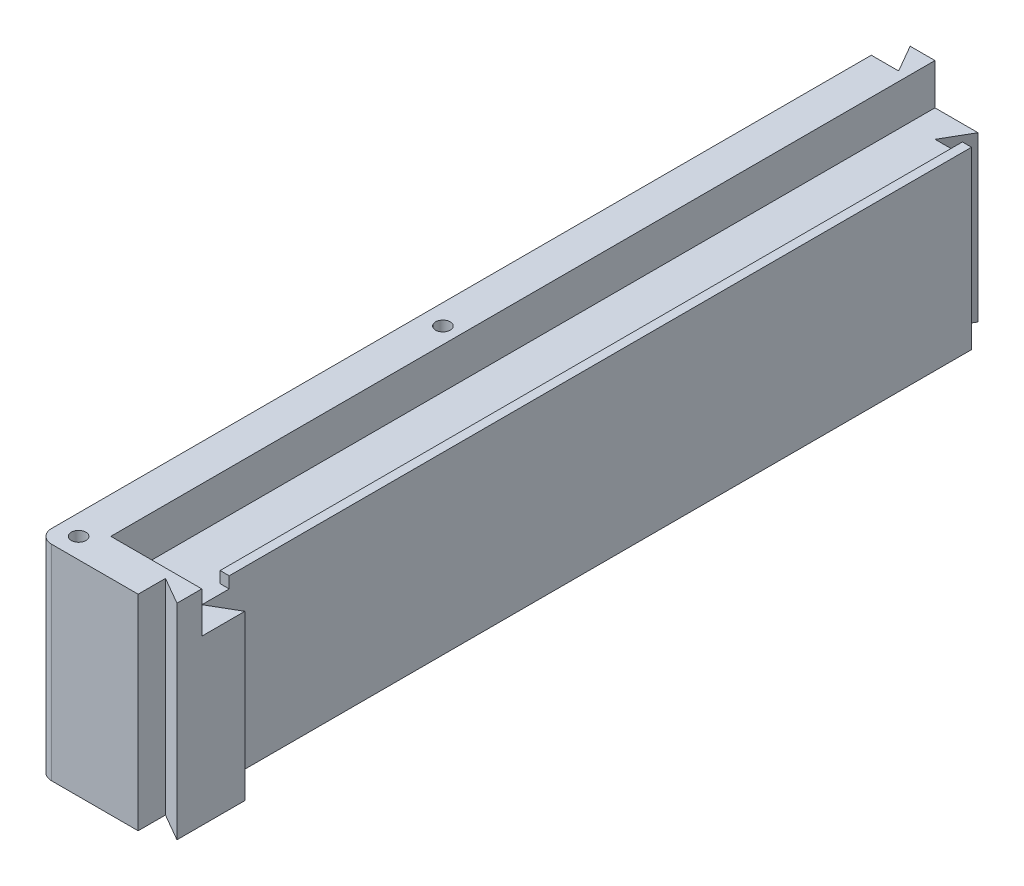
SolidWorks part; units mm, degrees
ref_plane "前视基准面" through (0, 0, 0) normal (0, 0, 1) x (1, 0, 0)
ref_plane "上视基准面" through (0, 0, 0) normal (0, 1, 0) x (1, 0, 0)
ref_plane "右视基准面" through (0, 0, 0) normal (1, 0, 0) x (0, 0, -1)
sketch "草图1" plane through (0, 0, 0) normal (0, 1, 0) x (1, 0, 0)
  line L1 (0, 0) -> (250, 0)
  line L2 (0, 0) -> (0, 350)
  line L3 (0, 350) -> (250, 350)
  line L4 (250, 0) -> (250, 350)
  line L12 (0, 350) -> (-1.1314, 351.1314)
  line L13 (-10, -10) -> (260, -10)
  line L14 (-10, -10) -> (-10, 360)
  line L15 (-10, 360) -> (260, 360)
  line L16 (260, -10) -> (260, 360)
  line L18 (14, 14) -> (236, 14)
  line L19 (14, 14) -> (14, 336)
  line L20 (14, 336) -> (236, 336)
  line L21 (236, 14) -> (236, 336)
  dimension "D7" = 135
  dimension "D1" = 350
  dimension "D2" = 250
  dimension "D3" = 10
  dimension "D4" = 10
  dimension "D5" = 10
  dimension "D6" = 10
  dimension "D8" = 14
  dimension "D9" = 14
  dimension "D10" = 14
  dimension "D11" = 14
extrude "凸台-拉伸2" add sketch "草图1" along normal blind 45
ref_plane "基准面1" through (0, 38.5, 0) normal (0, 1, 0) x (1, 0, 0)
sketch "草图4" plane through (0, 38.5, 0) normal (0, 1, 0) x (1, 0, 0)
  line L0 (0, 0) -> (250, 0) construction
  line L1 (0, 350) -> (250, 350) construction
  line L2 (250, 0) -> (250, 350) construction
  line L3 (0, 0) -> (0, 350) construction
  line L4 (0, 0) -> (250, 0)
  line L5 (0, 350) -> (250, 350)
  line L6 (250, 0) -> (250, 350)
  line L7 (0, 0) -> (0, 350)
  line L9 (14, 14) -> (236, 14)
  line L10 (14, 14) -> (14, 336)
  line L11 (14, 336) -> (236, 336)
  line L12 (236, 14) -> (236, 336)
  dimension "D1" = 14
  dimension "D2" = 14
  dimension "D3" = 14
  dimension "D4" = 14
extrude "凸台-拉伸3" add sketch "草图4" against normal blind 5
sketch "草图9" plane through (0, 38.5, 0) normal (0, 1, 0) x (1, 0, 0)
  line L0 (236, 336) -> (14, 336) construction
  line L1 (236, 14) -> (236, 336) construction
  line L2 (14, 14) -> (236, 14) construction
  line L3 (14, 336) -> (14, 14) construction
  line L4 (0, 350) -> (0, 0)
  line L5 (0, 0) -> (250, 0)
  line L6 (250, 0) -> (250, 350)
  line L7 (250, 350) -> (0, 350)
  line L8 (0, 350) -> (0, 0)
  line L9 (0, 0) -> (250, 0)
  line L10 (250, 0) -> (250, 350)
  line L11 (250, 350) -> (0, 350)
  line L12 (236, 336) -> (14, 336)
  line L13 (236, 14) -> (236, 336)
  line L14 (14, 14) -> (236, 14)
  line L15 (14, 336) -> (14, 14)
  line L16 (238, 12) -> (238, 338)
  line L17 (238, 338) -> (12, 338)
  line L18 (12, 338) -> (12, 12)
  line L19 (12, 12) -> (238, 12)
  line L20 (2, 348) -> (2, 2)
  line L21 (2, 2) -> (248, 2)
  line L22 (248, 2) -> (248, 348)
  line L23 (248, 348) -> (2, 348)
  dimension "D1" = 0
  dimension "D2" = 2
  dimension "D3" = 2
extrude "切除-拉伸3" cut sketch "草图9" against normal blind 2.5 contours L22 L23 L20 L21 L19 L18 L17 L16
sketch "草图12" plane through (0, 45, 0) normal (0, 1, 0) x (1, 0, 0)
  line L0 (0, 350) -> (-10, 360)
  line L1 (-10, 175) -> (260, 175)
  line L2 (-10, -10) -> (-10, 360) construction
  line L3 (260, -10) -> (260, 360) construction
  line L4 (125, -10) -> (125, 360)
  line L5 (-10, -10) -> (260, -10) construction
  line L6 (-10, 360) -> (260, 360) construction
  line L7 (0, 0) -> (-3.5355, -3.5355)
  line L8 (0, 0) -> (250, 0) construction
  circle A0 centre (-3.5355, 353.5355) radius 1.6
  circle A1 centre (-3.5355, -3.5355) radius 1.6
  circle A2 centre (253.5355, -3.5355) radius 1.6
  circle A3 centre (253.5355, 353.5355) radius 1.6
  point P28 (0, 0)
  dimension "D1" = 3.2
  dimension "D2" = 135
  dimension "D3" = 5
  dimension "D4" = 5
extrude "切除-拉伸5" cut sketch "草图12" against normal blind 109.5 contours A1 | L0 A0 | L0 A0 | A3 | A2
fillet "圆角1" radius 5 4 edges at (260, 22.5, -360) (260, 22.5, 10) (-10, 22.5, 10) (-10, 22.5, -360)
sketch "草图13" plane through (0, 33.5, 0) normal (0, -1, 0) x (1, 0, 0)
  line L0 (14, -336) -> (14, -14) construction
  line L1 (236, -336) -> (14, -336) construction
  line L2 (14, -14) -> (236, -14) construction
  line L3 (236, -14) -> (236, -336) construction
  line L4 (0, 0) -> (0, -350)
  line L5 (0, -350) -> (250, -350)
  line L6 (250, -350) -> (250, 0)
  line L7 (250, 0) -> (0, 0)
  line L8 (0, 0) -> (0, -350)
  line L9 (0, -350) -> (250, -350)
  line L10 (250, -350) -> (250, 0)
  line L11 (250, 0) -> (0, 0)
  line L12 (14, -336) -> (14, -14)
  line L13 (236, -336) -> (14, -336)
  line L14 (14, -14) -> (236, -14)
  line L15 (236, -14) -> (236, -336)
  dimension "D1" = 0
extrude "凸台-拉伸4" add sketch "草图13" along normal blind 33.5
sketch "草图14" plane through (0, 0, 0) normal (0, -1, 0) x (1, 0, 0)
  line L0 (14, -14) -> (14, 10)
  line L1 (-5, 10) -> (255, 10) construction
  line L2 (236, -14) -> (236, 10)
  line L3 (14, 2) -> (19.9756, 5.45)
  line L4 (19.9756, 5.45) -> (19.9756, -9.45)
  line L5 (19.9756, -9.45) -> (14, -6)
  line L6 (125, 10) -> (125, -14)
  line L7 (236, -14) -> (14, -14) construction
  line L8 (236, 2) -> (230.0244, 5.45)
  line L9 (230.0244, -9.45) -> (236, -6)
  line L10 (230.0244, 5.45) -> (230.0244, -9.45)
  line L11 (14, -175) -> (-10, -175)
  line L12 (14, -14) -> (14, -336) construction
  line L13 (14, -336) -> (14, -360)
  line L14 (14, -352) -> (19.9756, -355.45)
  line L15 (-5, -360) -> (255, -360)
  line L16 (260, -355) -> (260, 5)
  line L17 (255, 10) -> (-5, 10)
  line L18 (-10, 5) -> (-10, -355)
  line L19 (-5, -360) -> (255, -360)
  line L20 (260, -355) -> (260, 5)
  line L21 (255, 10) -> (-5, 10)
  line L22 (-10, 5) -> (-10, -355)
  line L23 (19.9756, -355.45) -> (19.9756, -340.55)
  line L24 (19.9756, -340.55) -> (14, -344)
  line L25 (-2, -175) -> (-5.45, -180.9756)
  line L26 (-5.45, -180.9756) -> (9.45, -180.9756)
  line L27 (9.45, -180.9756) -> (6, -175)
  arc A4 (255, -360) -> (260, -355) centre (255, -355) ccw
  arc A5 (260, 5) -> (255, 10) centre (255, 5) ccw
  arc A6 (-5, 10) -> (-10, 5) centre (-5, 5) ccw
  arc A7 (-10, -355) -> (-5, -360) centre (-5, -355) ccw
  arc A8 (255, -360) -> (260, -355) centre (255, -355) ccw
  arc A9 (260, 5) -> (255, 10) centre (255, 5) ccw
  arc A10 (-5, 10) -> (-10, 5) centre (-5, 5) ccw
  arc A11 (-10, -355) -> (-5, -360) centre (-5, -355) ccw
  point P10 (14, -2)
  point P45 (2, -175)
  circle M14 centre (-3.5355, -353.5355) radius 1.6
  line M16 (-5, -360) -> (255, -360)
  arc M17 (255, -360) -> (260, -355) centre (255, -355) ccw
  line M18 (260, -355) -> (260, 5)
  arc M19 (260, 5) -> (255, 10) centre (255, 5) ccw
  line M20 (255, 10) -> (-5, 10)
  line M22 (-10, 5) -> (-10, -355)
  arc M23 (-10, -355) -> (-5, -360) centre (-5, -355) ccw
  circle M24 centre (253.5355, -353.5355) radius 1.6
  circle M25 centre (253.5355, 3.5355) radius 1.6
  line M26 (236, -14) -> (236, -336)
  line M27 (236, -336) -> (14, -336)
  line M28 (14, -336) -> (14, -14)
  line M29 (14, -14) -> (236, -14)
  dimension "D1" = 4
  dimension "D2" = 4
  dimension "D3" = 60
  dimension "D4" = 60
  dimension "D5" = 14.9
  dimension "D7" = 4
  dimension "D8" = 4
  dimension "D9" = 60
  dimension "D10" = 60
  dimension "D11" = 14.9
  dimension "D6" = 0
extrude "切除-拉伸9" cut sketch "草图14" against normal blind 126.5 contours L27 L26 L25 L11 L13 M22 M23 M16 M28 M14 | L6 L0 L3 L4 L5 M20 M29 | L10 L8 L2 L6 L9 M20 M29 | L24 L23 L14 L13 L2 M16 M17 M18 M19 M20 M26 M27 M24 M25 | L8 L10 L9 L2 | M24 | L23 L24 L13 L14 | M14
sketch "草图15" plane through (0, 45, 0) normal (0, 1, 0) x (1, 0, 0)
  line L0 (-3.5355, -3.5355) -> (-3.5355, 76.4645)
  line L3 (0, 0) -> (0, 180.9756) construction
  circle A0 centre (-3.5355, 76.4645) radius 1.6
  dimension "D2" = 3.2
  dimension "D1" = 80
extrude "切除-拉伸10" cut sketch "草图15" against normal blind 50
sketch "草图16" plane through (0, 38.5, 0) normal (0, 1, 0) x (1, 0, 0)
  line L6 (0, 0) -> (19.9756, 0)
  line L7 (19.9756, 0) -> (19.9756, 2)
  line L8 (19.9756, 2) -> (2, 2)
  line L9 (2, 2) -> (2, 180.9756)
  line L10 (2, 180.9756) -> (0, 180.9756)
  line L11 (0, 180.9756) -> (0, 0)
  line L12 (0, 0) -> (19.9756, 0)
  line L13 (19.9756, 0) -> (19.9756, 2)
  line L14 (19.9756, 2) -> (2, 2)
  line L15 (2, 2) -> (2, 180.9756)
  line L16 (2, 180.9756) -> (0, 180.9756)
  line L17 (0, 180.9756) -> (0, 0)
  dimension "D1" = 0
extrude "切除-拉伸11" cut sketch "草图16" against normal blind 2.5
sketch "草图18" plane through (0, 45, 0) normal (0, 1, 0) x (1, 0, 0)
  line L10 (19.9756, -5.45) -> (19.9756, 0)
  line L11 (19.9756, 0) -> (0, 0)
  line L12 (0, 0) -> (0, 180.9756)
  line L13 (0, 180.9756) -> (-5.45, 180.9756)
  line L14 (-5.45, 180.9756) -> (-2, 175)
  line L15 (-2, 175) -> (-10, 175)
  line L16 (-10, 175) -> (-10, -5)
  line L17 (-5, -10) -> (14, -10)
  line L18 (14, -10) -> (14, -2)
  line L19 (14, -2) -> (19.9756, -5.45)
  line L20 (19.9756, -5.45) -> (19.9756, 0)
  line L21 (19.9756, 0) -> (0, 0)
  line L22 (0, 0) -> (0, 180.9756)
  line L23 (0, 180.9756) -> (-5.45, 180.9756)
  line L24 (-5.45, 180.9756) -> (-2, 175)
  line L25 (-2, 175) -> (-10, 175)
  line L26 (-10, 175) -> (-10, -5)
  line L27 (-5, -10) -> (14, -10)
  line L28 (14, -10) -> (14, -2)
  line L29 (14, -2) -> (19.9756, -5.45)
  line L30 (12, -8) -> (14, -8)
  line L31 (-8, 173) -> (-8, 175)
  line L40 (12, -2) -> (-2, -2)
  line L41 (-2, -2) -> (-2, 173)
  line L42 (-2, 173) -> (-8, 173)
  line L43 (-8, 173) -> (-8, -5)
  line L44 (-5, -8) -> (12, -8)
  line L45 (12, -8) -> (12, -2)
  line L46 (12, -2) -> (-2, -2)
  line L47 (-2, -2) -> (-2, 173)
  line L48 (-2, 173) -> (-8, 173)
  line L49 (-8, 173) -> (-8, -5)
  line L50 (-5, -8) -> (12, -8)
  line L51 (12, -8) -> (12, -2)
  arc A1 (-10, -5) -> (-5, -10) centre (-5, -5) ccw
  arc A2 (-10, -5) -> (-5, -10) centre (-5, -5) ccw
  arc A4 (-8, -5) -> (-5, -8) centre (-5, -5) ccw
  arc A5 (-8, -5) -> (-5, -8) centre (-5, -5) ccw
  line M26 (-10, 175) -> (-10, -5)
  arc M27 (-10, -5) -> (-5, -10) centre (-5, -5) ccw
  line M28 (-5, -10) -> (14, -10)
  line M29 (14, -10) -> (14, -2)
  dimension "D1" = 0
  dimension "D2" = 2
extrude "切除-拉伸12" cut sketch "草图18" against normal through all both and the other way through all contours A5 L49 L31 L25 L30 L50 M26 M27 M28 M29
equation "\"2。5\"=10"
